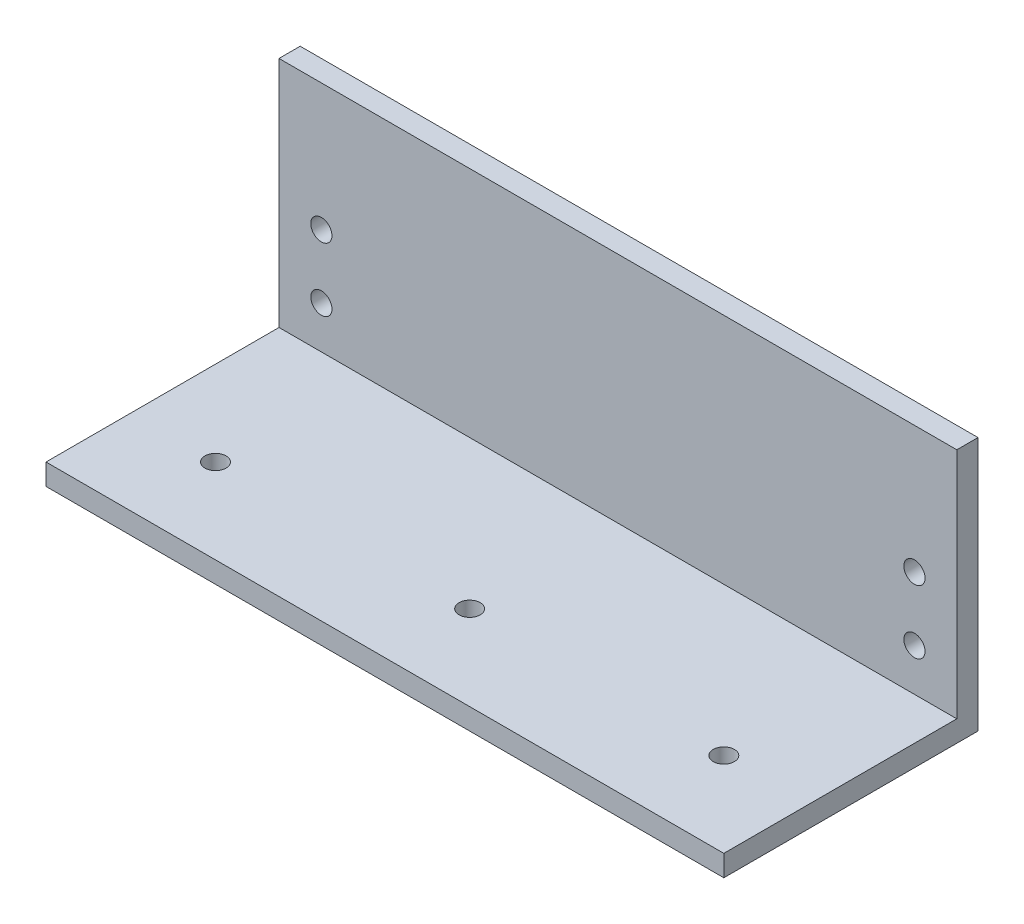
SolidWorks part; units mm, degrees
material "6061 Alloy"
ref_plane "Front Plane" through (0, 0, 0) normal (0, 0, 1) x (1, 0, 0)
ref_plane "Top Plane" through (0, 0, 0) normal (0, 1, 0) x (1, 0, 0)
ref_plane "Right Plane" through (0, 0, 0) normal (1, 0, 0) x (0, 0, -1)
sketch "Sketch2" plane through (0, 0, 0) normal (1, 0, 0) x (0, 0, -1)
  line L1 (0, 0) -> (76.2, 0)
  line L2 (0, 0) -> (0, 76.2)
  line L3 (0, 76.2) -> (76.2, 76.2)
  line L4 (76.2, 0) -> (76.2, 76.2)
  line L5 (0, 76.2) -> (69.85, 76.2)
  line L6 (0, 76.2) -> (0, 6.35)
  line L7 (0, 6.35) -> (69.85, 6.35)
  line L8 (69.85, 76.2) -> (69.85, 6.35)
  dimension "D1" = 76.2
  dimension "D2" = 76.2
  dimension "D3" = 6.35
  dimension "D4" = 6.35
extrude "Boss-Extrude2" add sketch "Sketch2" along normal blind 203.2 contours L3 L8 L7 L2 L1 L4
sketch "Sketch4" plane through (0, 0, -76.2) normal (0, 0, -1) x (-1, 0, 0)
  line L0 (-203.2, 0) -> (0, 0) construction
  line L1 (-203.2, 0) -> (-203.2, 76.2) construction
  circle A0 centre (-190.5, 19.05) radius 3.175
  circle A1 centre (-190.5, 38.1) radius 3.175
  circle A2 centre (-12.7, 19.05) radius 3.175
  circle A3 centre (-12.7, 38.1) radius 3.175
  dimension "D1" = 19.05
  dimension "D2" = 12.7
  dimension "D3" = 38.1
  dimension "D4" = 190.5
  dimension "D5" = 38.1
  dimension "D6" = 190.5
extrude "Cut-Extrude1" cut sketch "Sketch4" against normal blind 71.628
sketch "Sketch5" plane through (0, 6.35, 0) normal (0, 1, 0) x (1, 0, 0)
  line L0 (0, 0) -> (0, 69.85) construction
  line L1 (203.2, 0) -> (0, 0) construction
  circle A0 centre (25.4, 25.4) radius 3.175
  circle A1 centre (177.8, 25.4) radius 3.175
  circle A2 centre (101.6, 25.4) radius 3.175
  dimension "D1" = 177.8
  dimension "D2" = 6.35
  dimension "D3" = 25.4
  dimension "D4" = 101.6
  dimension "D5" = 25.4
  dimension "D6" = 25.4
  dimension "D7" = 25.4
extrude "Cut-Extrude2" cut sketch "Sketch5" against normal blind 244.602
